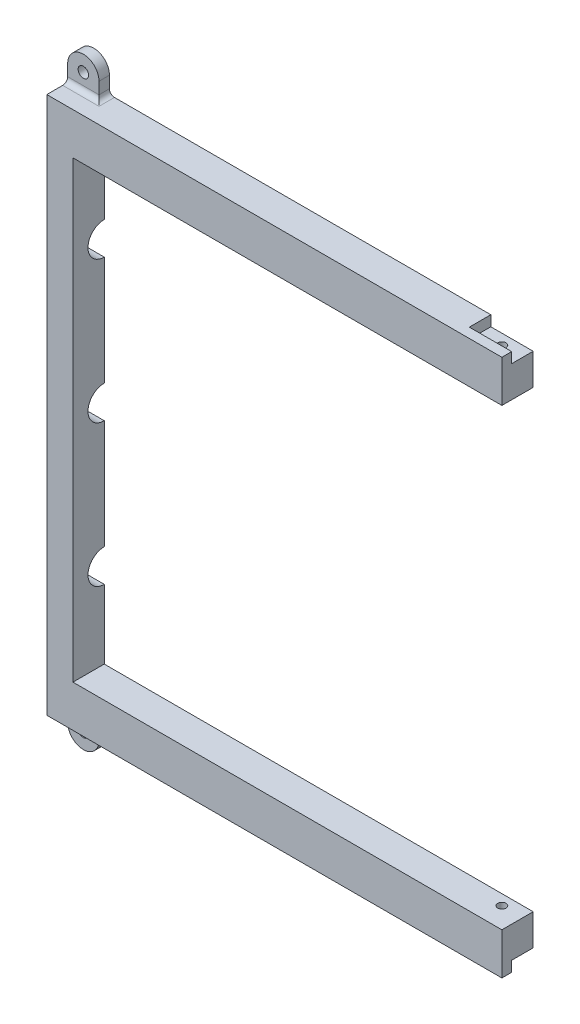
SolidWorks part; units mm, degrees
ref_plane "Front Plane" through (0, 0, 0) normal (0, 0, 1) x (1, 0, 0)
ref_plane "Top Plane" through (0, 0, 0) normal (0, 1, 0) x (1, 0, 0)
ref_plane "Right Plane" through (0, 0, 0) normal (1, 0, 0) x (0, 0, -1)
sketch "Sketch1" plane through (0, 0, 0) normal (0, 0, 1) x (1, 0, 0)
  line L0 (-138.43, 81.7626) -> (138.43, 81.7626)
  line L1 (-130.4798, -69.0626) -> (130.4798, -69.0626)
  line L2 (-130.4798, -69.0626) -> (-130.4798, 69.0626)
  line L3 (-130.4798, 69.0626) -> (130.4798, 69.0626)
  line L4 (130.4798, -69.0626) -> (130.4798, 69.0626)
  line L5 (-130.4798, -69.0626) -> (130.4798, 69.0626) construction
  line L6 (-130.4798, 69.0626) -> (130.4798, -69.0626) construction
  line L7 (138.43, -81.7626) -> (138.43, 81.7626)
  line L8 (-138.43, -81.7626) -> (138.43, -81.7626)
  line L9 (-138.43, -81.7626) -> (-138.43, 81.7626)
  point P0 (0, 0)
  dimension "D1" = 138.1252
  dimension "D2" = 260.9596
  dimension "D3" = 7.9502
  dimension "D4" = 7.9502
  dimension "D5" = 12.7
  dimension "D6" = 12.7
extrude "Boss-Extrude1" add sketch "Sketch1" along normal blind 9.525
sketch "Sketch2" plane through (138.43, 0, 0) normal (1, 0, 0) x (0, 0, -1)
  line L0 (0, -81.7626) -> (0, 81.7626) construction
  circle A0 centre (0, 0) radius 4.953
  circle A1 centre (0, 43.1038) radius 4.953
  circle A2 centre (0, -43.1038) radius 4.953
  dimension "D1" = 9.906
  dimension "D4" = 9.906
  dimension "D2" = 43.1038
  dimension "D3" = 43.1038
extrude "Cut-Extrude1" cut sketch "Sketch2" against normal through all
sketch "Sketch3" plane through (0, 0, 0) normal (0, 0, -1) x (-1, 0, 0)
  line L0 (-138.43, 81.7626) -> (-138.43, 86.8426)
  line L1 (-128.905, 81.7626) -> (-128.905, 86.8426)
  line L2 (-138.43, 81.7626) -> (138.43, 81.7626) construction
  line L3 (-138.43, 81.7626) -> (-128.905, 81.7626)
  arc A0 (-138.43, 86.8426) -> (-128.905, 86.8426) centre (-133.6675, 86.8426) cw
  circle A1 centre (-133.6675, 86.8426) radius 1.5875
  point P7 (-138.43, 84.3026)
  dimension "D3" = 3.175
  dimension "D1" = 5.08
  dimension "D2" = 9.525
extrude "Boss-Extrude2" add sketch "Sketch3" against normal blind 3.175
mirror "Mirror1" about plane through (0, 0, 0) normal (1, 0, 0) of "Boss-Extrude2"
mirror "Mirror2" about plane through (0, 0, 0) normal (0, 1, 0) of "Mirror1", "Boss-Extrude2"
fillet "Fillet1" radius 1.524 8 edges at (128.905, 81.7626, 1.5875) (-128.905, 81.7626, 1.5875) (-128.905, -81.7626, 1.5875) (-133.6675, -81.7626, 3.175) (128.905, -81.7626, 1.5875) (133.6675, -81.7626, 3.175) (133.6675, 81.7626, 3.175) (-133.6675, 81.7626, 3.175)
sketch "Sketch4" plane through (0, 81.7626, 0) normal (0, 1, 0) x (1, 0, 0)
  line L1 (-12.8905, -6.5405) -> (12.8905, -6.5405)
  line L2 (-12.8905, -6.5405) -> (-12.8905, 6.5405)
  line L3 (-12.8905, 6.5405) -> (12.8905, 6.5405)
  line L4 (12.8905, -6.5405) -> (12.8905, 6.5405)
  line L5 (-12.8905, -6.5405) -> (12.8905, 6.5405) construction
  line L6 (-12.8905, 6.5405) -> (12.8905, -6.5405) construction
  point P0 (0, 0)
  dimension "D1" = 25.781
  dimension "D2" = 13.081
extrude "Cut-Extrude2" cut sketch "Sketch4" against normal blind 3.175
sketch "Sketch5" plane through (0, 78.5876, 0) normal (0, 1, 0) x (1, 0, 0)
  circle A0 centre (6.35, -3.175) radius 1.27
  circle A1 centre (-6.35, -3.175) radius 1.27
  point P4 (0, 0)
  point P6 (0, 0)
  dimension "D3" = 2.54
  dimension "D1" = 6.35
  dimension "D2" = 3.175
  dimension "D4" = 6.35
  dimension "D5" = 3.175
extrude "Cut-Extrude3" cut sketch "Sketch5" against normal up to next
mirror "Mirror3" about plane through (0, 0, 0) normal (0, 1, 0) of "Cut-Extrude2", "Cut-Extrude3"
sketch "Sketch6" plane through (0, 0, 9.525) normal (0, 0, 1) x (1, 0, 0)
  line L0 (0, 0) -> (0, -104.9837)
  line L1 (0, -104.9837) -> (173.4852, -104.9837)
  line L2 (173.4852, -104.9837) -> (173.4852, 103.0002)
  line L3 (173.4852, 103.0002) -> (0, 103.0002)
  line L4 (0, 103.0002) -> (0, 0)
extrude "Cut-Extrude4" cut sketch "Sketch6" against normal through all
